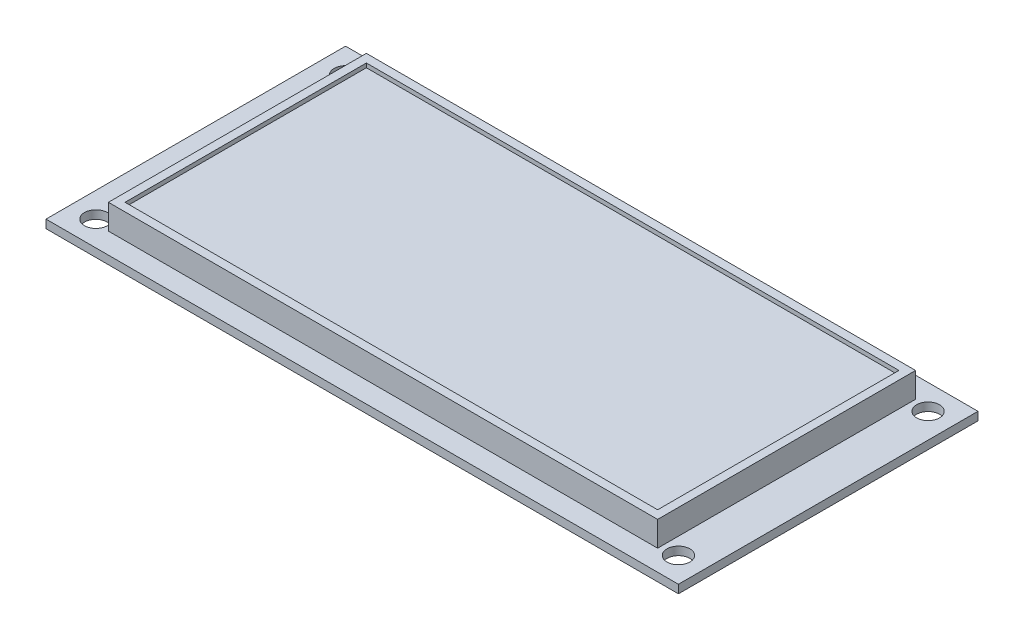
SolidWorks part; units mm, degrees
ref_plane "Front Plane" through (0, 0, 0) normal (0, 0, 1) x (1, 0, 0)
ref_plane "Top Plane" through (0, 0, 0) normal (0, 1, 0) x (1, 0, 0)
ref_plane "Right Plane" through (0, 0, 0) normal (1, 0, 0) x (0, 0, -1)
sketch "Sketch1" plane through (0, 0, 0) normal (0, 1, 0) x (1, 0, 0)
  line L1 (-38, 18) -> (38, 18)
  line L2 (-38, 18) -> (-38, -18)
  line L3 (-38, -18) -> (38, -18)
  line L4 (38, 18) -> (38, -18)
  line L5 (-38, 18) -> (38, -18) construction
  line L6 (-38, -18) -> (38, 18) construction
  point P0 (0, 0)
  dimension "D1" = 76
  dimension "D2" = 36
extrude "Boss-Extrude1" add sketch "Sketch1" along normal blind 1
sketch "Sketch2" plane through (0, 1, 0) normal (0, 1, 0) x (1, 0, 0)
  line L1 (-33, 15.5) -> (33, 15.5)
  line L2 (-33, 15.5) -> (-33, -15.5)
  line L3 (-33, -15.5) -> (33, -15.5)
  line L4 (33, 15.5) -> (33, -15.5)
  line L5 (-33, 15.5) -> (33, -15.5) construction
  line L6 (-33, -15.5) -> (33, 15.5) construction
  point P0 (0, 0)
  dimension "D1" = 66
  dimension "D2" = 31
extrude "Boss-Extrude2" add sketch "Sketch2" along normal blind 3
sketch "Sketch3" plane through (0, 4, 0) normal (0, 1, 0) x (1, 0, 0)
  line L0 (33, 15.5) -> (-33, 15.5) construction
  line L1 (-32, 14.5) -> (32, 14.5)
  line L2 (-32, 14.5) -> (-32, -14.5)
  line L3 (-32, -14.5) -> (32, -14.5)
  line L4 (32, 14.5) -> (32, -14.5)
  line L5 (-32, 14.5) -> (32, -14.5) construction
  line L6 (-32, -14.5) -> (32, 14.5) construction
  line L7 (-33, 15.5) -> (-33, -15.5) construction
  point P0 (0, 0)
  dimension "D1" = 1
  dimension "D2" = 1
extrude "Cut-Extrude1" cut sketch "Sketch3" against normal blind 0.5
sketch "Sketch4" plane through (0, 1, 0) normal (0, 1, 0) x (1, 0, 0)
  line L0 (0, 18) -> (0, -21.4318) construction
  line L1 (38, 18) -> (-38, 18) construction
  line L2 (-38, 18) -> (-38, -18) construction
  line L3 (-38, -18) -> (38, -18) construction
  circle A0 centre (-35, 15) radius 1.375
  circle A1 centre (-35, -15) radius 1.375
  circle A2 centre (35, -15) radius 1.375
  circle A3 centre (35, 15) radius 1.375
  dimension "D1" = 2.75
  dimension "D2" = 2.75
  dimension "D3" = 3
  dimension "D4" = 3
  dimension "D5" = 3
  dimension "D6" = 3
extrude "Cut-Extrude2" cut sketch "Sketch4" against normal blind 5
